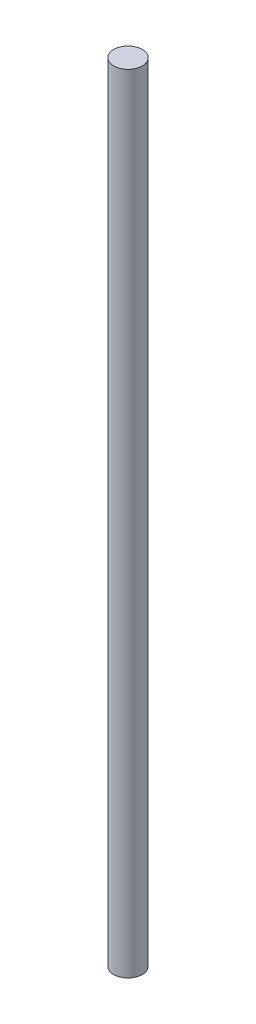
SolidWorks part; units mm, degrees
material "Plain Carbon Steel"
ref_plane "Front Plane" through (0, 0, 0) normal (0, 0, 1) x (1, 0, 0)
ref_plane "Top Plane" through (0, 0, 0) normal (0, 1, 0) x (1, 0, 0)
ref_plane "Right Plane" through (0, 0, 0) normal (1, 0, 0) x (0, 0, -1)
sketch "Sketch1" plane through (0, 0, 0) normal (0, 1, 0) x (1, 0, 0)
  circle A0 centre (0, 0) radius 0.3
  dimension "D1" = 0.6
extrude "Boss-Extrude1" add sketch "Sketch1" along normal blind 16.5
